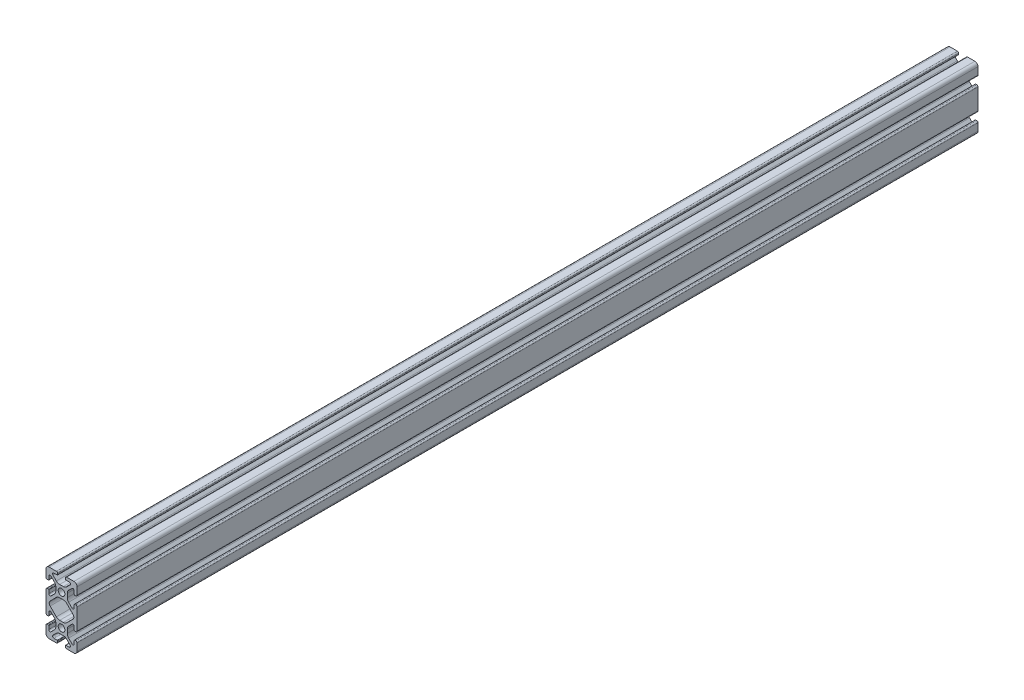
SolidWorks part; units mm, degrees
ref_plane "Front Plane" through (0, 0, 0) normal (0, 0, 1) x (1, 0, 0)
ref_plane "Top Plane" through (0, 0, 0) normal (0, 1, 0) x (1, 0, 0)
ref_plane "Right Plane" through (0, 0, 0) normal (1, 0, 0) x (0, 0, -1)
sketch "Sketch1" plane through (0, 0, 0) normal (0, 0, 1) x (1, 0, 0)
  line L0 (0, 10) -> (0, 20) construction
  line L1 (0, 10) -> (10, 10) construction
  line L2 (0, 10) -> (-10, 20) construction
  line L3 (-8, 20) -> (-3.3, 20)
  line L4 (-10, 20) -> (0, 20) construction
  line L6 (-2.8, 18.2) -> (-4.9051, 18.2)
  line L10 (0, 13.7) -> (-1.2022, 13.7)
  line L11 (-3.3236, 14.5787) -> (-5.5025, 16.7576)
  line L24 (0, 10) -> (-10, 10) construction
  line L25 (-10, 10) -> (0, 10) construction
  line L27 (-10, 0) -> (-10, 20) construction
  line L28 (0, 20) -> (10, 20) construction
  line L29 (-2.5, 18.5) -> (-2.5, 19.2)
  line L30 (-10, -20) -> (10, -20) construction
  line L31 (0, 20) -> (0, -20) construction
  arc A0 (-9.4142, 19.4142) -> (-8, 20) centre (-8, 18) cw
  arc A5 (-3.3, 20) -> (-2.5, 19.2) centre (-3.3, 19.2) cw
  arc A6 (-1.2022, 13.7) -> (-3.3236, 14.5787) centre (-1.2022, 16.7) cw
  circle A16 centre (0, 10) radius 2.15
  arc A18 (-5.5025, 16.7576) -> (-4.9051, 18.2) centre (-4.9051, 17.3551) cw
  arc A20 (-2.8, 18.2) -> (-2.5, 18.5) centre (-2.8, 18.5) ccw
  point P15 (0, -20)
  point P24 (0, 0)
  point P42 (-2.4449, 13.7)
  point P80 (-10, 10)
  dimension "D11" = 2
  dimension "D15" = 3
  dimension "Center Hole Diameter" = 4.3
  dimension "D7" = 0.8
  dimension "D8" = 0.3
  dimension "D4" = 0.8449
  dimension "D1" = 45
  dimension "Rail Width" = 20
  dimension "T-Slot Depth" = 6.3
  dimension "D9" = 1.8
  dimension "D23" = 7.4
  dimension "D5" = 11.5
  dimension "T-Slot Width" = 5
  dimension "D3" = 1.775
  dimension "D6" = 9.8102
  dimension "Rail Height" = 40
sketch "Sketch2" plane through (0, 0, 0) normal (1, 0, 0) x (0, 0, -1)
  line L0 (-304.8, 0) -> (304.8, 0)
  line L1 (-304.8, -20) -> (-304.8, 20)
  line L2 (0, 10) -> (0, 20) construction
  line L3 (0, 0) -> (0, 20) construction
  line L4 (304.8, -20) -> (304.8, 20)
  line L5 (-10, 10) -> (10, 10) construction
  point P0 (-279.8, 0)
  point P3 (0, 0)
  point P7 (279.8, 0)
  point P11 (-304.8, 0)
  point P14 (304.8, 0)
  point P23 (0, 10)
  dimension "D1" = 25
  dimension "Length" = 609.6
sketch "Sketch3" plane through (0, 0, 0) normal (0, 0, 1) x (1, 0, 0)
  line L0 (-2.5, 18.5) -> (-2.5, 19.2) construction
  line L1 (0, 10) -> (-10, 20) construction
  line L2 (0, 10) -> (-10, 20) construction
  line L5 (-8, 20) -> (-3.3, 20) construction
  line L6 (-2.8, 18.2) -> (-4.9051, 18.2) construction
  line L7 (-8.5, 7.5) -> (-9.2, 7.5)
  line L17 (-2.5, 18.5) -> (-2.5, 19.2)
  line L19 (-2.8, 18.2) -> (-4.9051, 18.2)
  line L21 (-3.7, 10) -> (0, 10) construction
  line L22 (-3.7, 8.7978) -> (-3.7, 11.2022)
  line L23 (-4.5787, 13.3236) -> (-6.7576, 15.5025)
  line L42 (-3.3236, 14.5787) -> (-5.5025, 16.7576) construction
  line L43 (0, 13.7) -> (-1.2022, 13.7) construction
  line L44 (-8, 20) -> (-3.3, 20)
  line L47 (-3.3236, 14.5787) -> (-5.5025, 16.7576)
  line L48 (1.2022, 13.7) -> (-1.2022, 13.7)
  line L59 (0, 13.7) -> (0, 12.15) construction
  line L60 (-10, 18) -> (-10, 13.3)
  line L61 (-8.2, 12.8) -> (-8.2, 14.9051)
  line L62 (-8.5, 12.5) -> (-9.2, 12.5)
  line L63 (-8.2, 7.2) -> (-8.2, 5.0949)
  line L64 (-10, 0) -> (-10, 6.7)
  line L65 (1.2022, 6.3) -> (-1.2022, 6.3)
  line L66 (-3.3236, 5.4213) -> (-7.3307, 1.4142)
  line L68 (-4.5787, 6.6764) -> (-6.7576, 4.4975)
  line L73 (10, 0) -> (-10, 0) construction
  line L78 (4.5787, 6.6764) -> (6.7576, 4.4975)
  line L79 (3.3236, 5.4213) -> (7.3307, 1.4142)
  line L81 (10, 0) -> (10, 6.7)
  line L82 (8.2, 7.2) -> (8.2, 5.0949)
  line L83 (8.5, 12.5) -> (9.2, 12.5)
  line L84 (8.2, 12.8) -> (8.2, 14.9051)
  line L85 (10, 18) -> (10, 13.3)
  line L87 (3.3236, 14.5787) -> (5.5025, 16.7576)
  line L88 (8, 20) -> (3.3, 20)
  line L89 (4.5787, 13.3236) -> (6.7576, 15.5025)
  line L90 (3.7, 8.7978) -> (3.7, 11.2022)
  line L91 (2.8, 18.2) -> (4.9051, 18.2)
  line L92 (2.5, 18.5) -> (2.5, 19.2)
  line L93 (8.5, 7.5) -> (9.2, 7.5)
  line L94 (-10, 0) -> (-7.9165, 0)
  line L96 (7.9165, 0) -> (10, 0)
  arc A0 (-8, 20) -> (-9.4142, 19.4142) centre (-8, 18) ccw construction
  arc A1 (-2.8, 18.2) -> (-2.5, 18.5) centre (-2.8, 18.5) ccw construction
  arc A3 (-2.8, 18.2) -> (-2.5, 18.5) centre (-2.8, 18.5) ccw
  arc A5 (-8, 20) -> (-10, 18) centre (-8, 18) ccw
  arc A10 (-3.3236, 5.4213) -> (-1.2022, 6.3) centre (-1.2022, 3.3) cw
  circle A13 centre (0, 10) radius 2.15 construction
  circle A14 centre (0, 10) radius 2.15
  arc A15 (-4.5787, 13.3236) -> (-3.7, 11.2022) centre (-6.7, 11.2022) cw
  arc A16 (-8.2, 14.9051) -> (-6.7576, 15.5025) centre (-7.3551, 14.9051) cw
  arc A17 (-9.2, 12.5) -> (-10, 13.3) centre (-9.2, 13.3) cw
  arc A18 (-8.2, 12.8) -> (-8.5, 12.5) centre (-8.5, 12.8) cw
  arc A36 (-2.5, 19.2) -> (-3.3, 20) centre (-3.3, 19.2) ccw construction
  arc A38 (-4.9051, 18.2) -> (-5.5025, 16.7576) centre (-4.9051, 17.3551) ccw construction
  arc A39 (-3.3236, 14.5787) -> (-1.2022, 13.7) centre (-1.2022, 16.7) ccw construction
  arc A41 (-2.5, 19.2) -> (-3.3, 20) centre (-3.3, 19.2) ccw
  arc A43 (-4.9051, 18.2) -> (-5.5025, 16.7576) centre (-4.9051, 17.3551) ccw
  arc A44 (-3.3236, 14.5787) -> (-1.2022, 13.7) centre (-1.2022, 16.7) ccw
  arc A47 (-8.2, 7.2) -> (-8.5, 7.5) centre (-8.5, 7.2) ccw
  arc A48 (-9.2, 7.5) -> (-10, 6.7) centre (-9.2, 6.7) ccw
  arc A49 (-8.2, 5.0949) -> (-6.7576, 4.4975) centre (-7.3551, 5.0949) ccw
  arc A50 (-4.5787, 6.6764) -> (-3.7, 8.7978) centre (-6.7, 8.7978) ccw
  arc A54 (-7.9165, 0) -> (-7.3307, 1.4142) centre (-5.9165, 0) cw
  arc A57 (7.9165, 0) -> (7.3307, 1.4142) centre (5.9165, 0) ccw
  arc A58 (4.5787, 6.6764) -> (3.7, 8.7978) centre (6.7, 8.7978) cw
  arc A59 (8.2, 5.0949) -> (6.7576, 4.4975) centre (7.3551, 5.0949) cw
  arc A60 (9.2, 7.5) -> (10, 6.7) centre (9.2, 6.7) cw
  arc A61 (8.2, 7.2) -> (8.5, 7.5) centre (8.5, 7.2) cw
  arc A62 (3.3236, 14.5787) -> (1.2022, 13.7) centre (1.2022, 16.7) cw
  arc A63 (4.9051, 18.2) -> (5.5025, 16.7576) centre (4.9051, 17.3551) cw
  arc A64 (2.5, 19.2) -> (3.3, 20) centre (3.3, 19.2) cw
  arc A65 (8.2, 12.8) -> (8.5, 12.5) centre (8.5, 12.8) ccw
  arc A66 (9.2, 12.5) -> (10, 13.3) centre (9.2, 13.3) ccw
  arc A67 (8.2, 14.9051) -> (6.7576, 15.5025) centre (7.3551, 14.9051) ccw
  arc A68 (4.5787, 13.3236) -> (3.7, 11.2022) centre (6.7, 11.2022) ccw
  arc A70 (3.3236, 5.4213) -> (1.2022, 6.3) centre (1.2022, 3.3) ccw
  arc A71 (8, 20) -> (10, 18) centre (8, 18) cw
  arc A72 (2.8, 18.2) -> (2.5, 18.5) centre (2.8, 18.5) cw
  point P59 (-10, 2)
  point P71 (0, 0)
  point P116 (0, 6.3)
extrude "Boss-Extrude1" add sketch "Sketch3" along normal mid plane 609.6
pattern_circular "CirPattern1" count 2 over 360 about axis through (0, 0, 0) along (0, 0, 1) of "Boss-Extrude1"
sketch "Sketch4" plane through (0, 0, 304.8) normal (0, 0, 1) x (1, 0, 0)
  line L0 (7.3307, -1.4142) -> (3.3236, -5.4213) construction
  line L1 (-3.3236, -5.4213) -> (-7.3307, -1.4142) construction
  line L2 (1.2022, -6.3) -> (-1.2022, -6.3) construction
  line L3 (3.3236, 5.4213) -> (7.3307, 1.4142) construction
  line L4 (-1.2022, 6.3) -> (1.2022, 6.3) construction
  line L5 (-7.3307, 1.4142) -> (-3.3236, 5.4213) construction
  line L6 (7.3307, -1.4142) -> (3.3236, -5.4213)
  line L7 (-3.3236, -5.4213) -> (-7.3307, -1.4142)
  line L8 (1.2022, -6.3) -> (-1.2022, -6.3)
  line L9 (3.3236, 5.4213) -> (7.3307, 1.4142)
  line L10 (-1.2022, 6.3) -> (1.2022, 6.3)
  line L11 (-7.3307, 1.4142) -> (-3.3236, 5.4213)
  line L52 (-2.5, 18.5) -> (-2.5, 19.2)
  line L53 (-3.3, 20) -> (-8, 20)
  line L54 (-10, 18) -> (-10, 13.3)
  line L55 (-9.2, 12.5) -> (-8.5, 12.5)
  line L56 (-8.2, 12.8) -> (-8.2, 14.9051)
  line L57 (-6.7576, 15.5025) -> (-4.5787, 13.3236)
  line L58 (-3.7, 11.2022) -> (-3.7, 8.7978)
  line L59 (-4.5787, 6.6764) -> (-6.7576, 4.4975)
  line L60 (-8.2, 5.0949) -> (-8.2, 7.2)
  line L61 (-8.5, 7.5) -> (-9.2, 7.5)
  line L62 (-10, 6.7) -> (-10, -6.7)
  line L63 (-9.2, -7.5) -> (-8.5, -7.5)
  line L64 (-8.2, -7.2) -> (-8.2, -5.0949)
  line L65 (-6.7576, -4.4975) -> (-4.5787, -6.6764)
  line L66 (-3.7, -8.7978) -> (-3.7, -11.2022)
  line L67 (-4.5787, -13.3236) -> (-6.7576, -15.5025)
  line L68 (-8.2, -14.9051) -> (-8.2, -12.8)
  line L69 (-8.5, -12.5) -> (-9.2, -12.5)
  line L70 (-10, -13.3) -> (-10, -18)
  line L71 (-8, -20) -> (-3.3, -20)
  line L72 (-2.5, -19.2) -> (-2.5, -18.5)
  line L73 (-2.8, -18.2) -> (-4.9051, -18.2)
  line L74 (-5.5025, -16.7576) -> (-3.3236, -14.5787)
  line L75 (-1.2022, -13.7) -> (1.2022, -13.7)
  line L76 (3.3236, -14.5787) -> (5.5025, -16.7576)
  line L77 (4.9051, -18.2) -> (2.8, -18.2)
  line L78 (2.5, -18.5) -> (2.5, -19.2)
  line L79 (3.3, -20) -> (8, -20)
  line L80 (10, -18) -> (10, -13.3)
  line L81 (9.2, -12.5) -> (8.5, -12.5)
  line L82 (8.2, -12.8) -> (8.2, -14.9051)
  line L83 (6.7576, -15.5025) -> (4.5787, -13.3236)
  line L84 (3.7, -11.2022) -> (3.7, -8.7978)
  line L85 (4.5787, -6.6764) -> (6.7576, -4.4975)
  line L86 (8.2, -5.0949) -> (8.2, -7.2)
  line L87 (8.5, -7.5) -> (9.2, -7.5)
  line L88 (10, -6.7) -> (10, 6.7)
  line L89 (9.2, 7.5) -> (8.5, 7.5)
  line L90 (8.2, 7.2) -> (8.2, 5.0949)
  line L91 (6.7576, 4.4975) -> (4.5787, 6.6764)
  line L92 (3.7, 8.7978) -> (3.7, 11.2022)
  line L93 (4.5787, 13.3236) -> (6.7576, 15.5025)
  line L94 (8.2, 14.9051) -> (8.2, 12.8)
  line L95 (8.5, 12.5) -> (9.2, 12.5)
  line L96 (10, 13.3) -> (10, 18)
  line L97 (8, 20) -> (3.3, 20)
  line L98 (2.5, 19.2) -> (2.5, 18.5)
  line L99 (2.8, 18.2) -> (4.9051, 18.2)
  line L100 (5.5025, 16.7576) -> (3.3236, 14.5787)
  line L101 (1.2022, 13.7) -> (-1.2022, 13.7)
  line L102 (-3.3236, 14.5787) -> (-5.5025, 16.7576)
  line L103 (-4.9051, 18.2) -> (-2.8, 18.2)
  line L104 (-2.5, 18.5) -> (-2.5, 19.2)
  line L105 (-3.3, 20) -> (-8, 20)
  line L106 (-10, 18) -> (-10, 13.3)
  line L107 (-9.2, 12.5) -> (-8.5, 12.5)
  line L108 (-8.2, 12.8) -> (-8.2, 14.9051)
  line L109 (-6.7576, 15.5025) -> (-4.5787, 13.3236)
  line L110 (-3.7, 11.2022) -> (-3.7, 8.7978)
  line L111 (-4.5787, 6.6764) -> (-6.7576, 4.4975)
  line L112 (-8.2, 5.0949) -> (-8.2, 7.2)
  line L113 (-8.5, 7.5) -> (-9.2, 7.5)
  line L114 (-10, 6.7) -> (-10, -6.7)
  line L115 (-9.2, -7.5) -> (-8.5, -7.5)
  line L116 (-8.2, -7.2) -> (-8.2, -5.0949)
  line L117 (-6.7576, -4.4975) -> (-4.5787, -6.6764)
  line L118 (-3.7, -8.7978) -> (-3.7, -11.2022)
  line L119 (-4.5787, -13.3236) -> (-6.7576, -15.5025)
  line L120 (-8.2, -14.9051) -> (-8.2, -12.8)
  line L121 (-8.5, -12.5) -> (-9.2, -12.5)
  line L122 (-10, -13.3) -> (-10, -18)
  line L123 (-8, -20) -> (-3.3, -20)
  line L124 (-2.5, -19.2) -> (-2.5, -18.5)
  line L125 (-2.8, -18.2) -> (-4.9051, -18.2)
  line L126 (-5.5025, -16.7576) -> (-3.3236, -14.5787)
  line L127 (-1.2022, -13.7) -> (1.2022, -13.7)
  line L128 (3.3236, -14.5787) -> (5.5025, -16.7576)
  line L129 (4.9051, -18.2) -> (2.8, -18.2)
  line L130 (2.5, -18.5) -> (2.5, -19.2)
  line L131 (3.3, -20) -> (8, -20)
  line L132 (10, -18) -> (10, -13.3)
  line L133 (9.2, -12.5) -> (8.5, -12.5)
  line L134 (8.2, -12.8) -> (8.2, -14.9051)
  line L135 (6.7576, -15.5025) -> (4.5787, -13.3236)
  line L136 (3.7, -11.2022) -> (3.7, -8.7978)
  line L137 (4.5787, -6.6764) -> (6.7576, -4.4975)
  line L138 (8.2, -5.0949) -> (8.2, -7.2)
  line L139 (8.5, -7.5) -> (9.2, -7.5)
  line L140 (10, -6.7) -> (10, 6.7)
  line L141 (9.2, 7.5) -> (8.5, 7.5)
  line L142 (8.2, 7.2) -> (8.2, 5.0949)
  line L143 (6.7576, 4.4975) -> (4.5787, 6.6764)
  line L144 (3.7, 8.7978) -> (3.7, 11.2022)
  line L145 (4.5787, 13.3236) -> (6.7576, 15.5025)
  line L146 (8.2, 14.9051) -> (8.2, 12.8)
  line L147 (8.5, 12.5) -> (9.2, 12.5)
  line L148 (10, 13.3) -> (10, 18)
  line L149 (8, 20) -> (3.3, 20)
  line L150 (2.5, 19.2) -> (2.5, 18.5)
  line L151 (2.8, 18.2) -> (4.9051, 18.2)
  line L152 (5.5025, 16.7576) -> (3.3236, 14.5787)
  line L153 (1.2022, 13.7) -> (-1.2022, 13.7)
  line L154 (-3.3236, 14.5787) -> (-5.5025, 16.7576)
  line L155 (-4.9051, 18.2) -> (-2.8, 18.2)
  circle A0 centre (0, 10) radius 2.15 construction
  arc A1 (-7.3307, 1.4142) -> (-7.3307, -1.4142) centre (-5.9165, 0) ccw construction
  arc A2 (-3.3236, -5.4213) -> (-1.2022, -6.3) centre (-1.2022, -3.3) ccw construction
  arc A3 (1.2022, -6.3) -> (3.3236, -5.4213) centre (1.2022, -3.3) ccw construction
  circle A4 centre (0, -10) radius 2.15 construction
  arc A5 (7.3307, -1.4142) -> (7.3307, 1.4142) centre (5.9165, 0) ccw construction
  arc A6 (3.3236, 5.4213) -> (1.2022, 6.3) centre (1.2022, 3.3) ccw construction
  arc A7 (-1.2022, 6.3) -> (-3.3236, 5.4213) centre (-1.2022, 3.3) ccw construction
  circle A8 centre (0, 10) radius 2.15
  arc A9 (-7.3307, 1.4142) -> (-7.3307, -1.4142) centre (-5.9165, 0) ccw
  arc A10 (-3.3236, -5.4213) -> (-1.2022, -6.3) centre (-1.2022, -3.3) ccw
  arc A11 (1.2022, -6.3) -> (3.3236, -5.4213) centre (1.2022, -3.3) ccw
  circle A12 centre (0, -10) radius 2.15
  arc A13 (7.3307, -1.4142) -> (7.3307, 1.4142) centre (5.9165, 0) ccw
  arc A14 (3.3236, 5.4213) -> (1.2022, 6.3) centre (1.2022, 3.3) ccw
  arc A15 (-1.2022, 6.3) -> (-3.3236, 5.4213) centre (-1.2022, 3.3) ccw
  arc A52 (-2.8, 18.2) -> (-2.5, 18.5) centre (-2.8, 18.5) ccw
  arc A53 (-2.5, 19.2) -> (-3.3, 20) centre (-3.3, 19.2) ccw
  arc A54 (-8, 20) -> (-10, 18) centre (-8, 18) ccw
  arc A55 (-10, 13.3) -> (-9.2, 12.5) centre (-9.2, 13.3) ccw
  arc A56 (-8.5, 12.5) -> (-8.2, 12.8) centre (-8.5, 12.8) ccw
  arc A57 (-6.7576, 15.5025) -> (-8.2, 14.9051) centre (-7.3551, 14.9051) ccw
  arc A58 (-3.7, 11.2022) -> (-4.5787, 13.3236) centre (-6.7, 11.2022) ccw
  arc A59 (-4.5787, 6.6764) -> (-3.7, 8.7978) centre (-6.7, 8.7978) ccw
  arc A60 (-8.2, 5.0949) -> (-6.7576, 4.4975) centre (-7.3551, 5.0949) ccw
  arc A61 (-8.2, 7.2) -> (-8.5, 7.5) centre (-8.5, 7.2) ccw
  arc A62 (-9.2, 7.5) -> (-10, 6.7) centre (-9.2, 6.7) ccw
  arc A63 (-10, -6.7) -> (-9.2, -7.5) centre (-9.2, -6.7) ccw
  arc A64 (-8.5, -7.5) -> (-8.2, -7.2) centre (-8.5, -7.2) ccw
  arc A65 (-6.7576, -4.4975) -> (-8.2, -5.0949) centre (-7.3551, -5.0949) ccw
  arc A66 (-3.7, -8.7978) -> (-4.5787, -6.6764) centre (-6.7, -8.7978) ccw
  arc A67 (-4.5787, -13.3236) -> (-3.7, -11.2022) centre (-6.7, -11.2022) ccw
  arc A68 (-8.2, -14.9051) -> (-6.7576, -15.5025) centre (-7.3551, -14.9051) ccw
  arc A69 (-8.2, -12.8) -> (-8.5, -12.5) centre (-8.5, -12.8) ccw
  arc A70 (-9.2, -12.5) -> (-10, -13.3) centre (-9.2, -13.3) ccw
  arc A71 (-10, -18) -> (-8, -20) centre (-8, -18) ccw
  arc A72 (-3.3, -20) -> (-2.5, -19.2) centre (-3.3, -19.2) ccw
  arc A73 (-2.5, -18.5) -> (-2.8, -18.2) centre (-2.8, -18.5) ccw
  arc A74 (-5.5025, -16.7576) -> (-4.9051, -18.2) centre (-4.9051, -17.3551) ccw
  arc A75 (-1.2022, -13.7) -> (-3.3236, -14.5787) centre (-1.2022, -16.7) ccw
  arc A76 (3.3236, -14.5787) -> (1.2022, -13.7) centre (1.2022, -16.7) ccw
  arc A77 (4.9051, -18.2) -> (5.5025, -16.7576) centre (4.9051, -17.3551) ccw
  arc A78 (2.8, -18.2) -> (2.5, -18.5) centre (2.8, -18.5) ccw
  arc A79 (2.5, -19.2) -> (3.3, -20) centre (3.3, -19.2) ccw
  arc A80 (8, -20) -> (10, -18) centre (8, -18) ccw
  arc A81 (10, -13.3) -> (9.2, -12.5) centre (9.2, -13.3) ccw
  arc A82 (8.5, -12.5) -> (8.2, -12.8) centre (8.5, -12.8) ccw
  arc A83 (6.7576, -15.5025) -> (8.2, -14.9051) centre (7.3551, -14.9051) ccw
  arc A84 (3.7, -11.2022) -> (4.5787, -13.3236) centre (6.7, -11.2022) ccw
  arc A85 (4.5787, -6.6764) -> (3.7, -8.7978) centre (6.7, -8.7978) ccw
  arc A86 (8.2, -5.0949) -> (6.7576, -4.4975) centre (7.3551, -5.0949) ccw
  arc A87 (8.2, -7.2) -> (8.5, -7.5) centre (8.5, -7.2) ccw
  arc A88 (9.2, -7.5) -> (10, -6.7) centre (9.2, -6.7) ccw
  arc A89 (10, 6.7) -> (9.2, 7.5) centre (9.2, 6.7) ccw
  arc A90 (8.5, 7.5) -> (8.2, 7.2) centre (8.5, 7.2) ccw
  arc A91 (6.7576, 4.4975) -> (8.2, 5.0949) centre (7.3551, 5.0949) ccw
  arc A92 (3.7, 8.7978) -> (4.5787, 6.6764) centre (6.7, 8.7978) ccw
  arc A93 (4.5787, 13.3236) -> (3.7, 11.2022) centre (6.7, 11.2022) ccw
  arc A94 (8.2, 14.9051) -> (6.7576, 15.5025) centre (7.3551, 14.9051) ccw
  arc A95 (8.2, 12.8) -> (8.5, 12.5) centre (8.5, 12.8) ccw
  arc A96 (9.2, 12.5) -> (10, 13.3) centre (9.2, 13.3) ccw
  arc A97 (10, 18) -> (8, 20) centre (8, 18) ccw
  arc A98 (3.3, 20) -> (2.5, 19.2) centre (3.3, 19.2) ccw
  arc A99 (2.5, 18.5) -> (2.8, 18.2) centre (2.8, 18.5) ccw
  arc A100 (5.5025, 16.7576) -> (4.9051, 18.2) centre (4.9051, 17.3551) ccw
  arc A101 (1.2022, 13.7) -> (3.3236, 14.5787) centre (1.2022, 16.7) ccw
  arc A102 (-3.3236, 14.5787) -> (-1.2022, 13.7) centre (-1.2022, 16.7) ccw
  arc A103 (-4.9051, 18.2) -> (-5.5025, 16.7576) centre (-4.9051, 17.3551) ccw
  arc A104 (-2.8, 18.2) -> (-2.5, 18.5) centre (-2.8, 18.5) ccw
  arc A105 (-2.5, 19.2) -> (-3.3, 20) centre (-3.3, 19.2) ccw
  arc A106 (-8, 20) -> (-10, 18) centre (-8, 18) ccw
  arc A107 (-10, 13.3) -> (-9.2, 12.5) centre (-9.2, 13.3) ccw
  arc A108 (-8.5, 12.5) -> (-8.2, 12.8) centre (-8.5, 12.8) ccw
  arc A109 (-6.7576, 15.5025) -> (-8.2, 14.9051) centre (-7.3551, 14.9051) ccw
  arc A110 (-3.7, 11.2022) -> (-4.5787, 13.3236) centre (-6.7, 11.2022) ccw
  arc A111 (-4.5787, 6.6764) -> (-3.7, 8.7978) centre (-6.7, 8.7978) ccw
  arc A112 (-8.2, 5.0949) -> (-6.7576, 4.4975) centre (-7.3551, 5.0949) ccw
  arc A113 (-8.2, 7.2) -> (-8.5, 7.5) centre (-8.5, 7.2) ccw
  arc A114 (-9.2, 7.5) -> (-10, 6.7) centre (-9.2, 6.7) ccw
  arc A115 (-10, -6.7) -> (-9.2, -7.5) centre (-9.2, -6.7) ccw
  arc A116 (-8.5, -7.5) -> (-8.2, -7.2) centre (-8.5, -7.2) ccw
  arc A117 (-6.7576, -4.4975) -> (-8.2, -5.0949) centre (-7.3551, -5.0949) ccw
  arc A118 (-3.7, -8.7978) -> (-4.5787, -6.6764) centre (-6.7, -8.7978) ccw
  arc A119 (-4.5787, -13.3236) -> (-3.7, -11.2022) centre (-6.7, -11.2022) ccw
  arc A120 (-8.2, -14.9051) -> (-6.7576, -15.5025) centre (-7.3551, -14.9051) ccw
  arc A121 (-8.2, -12.8) -> (-8.5, -12.5) centre (-8.5, -12.8) ccw
  arc A122 (-9.2, -12.5) -> (-10, -13.3) centre (-9.2, -13.3) ccw
  arc A123 (-10, -18) -> (-8, -20) centre (-8, -18) ccw
  arc A124 (-3.3, -20) -> (-2.5, -19.2) centre (-3.3, -19.2) ccw
  arc A125 (-2.5, -18.5) -> (-2.8, -18.2) centre (-2.8, -18.5) ccw
  arc A126 (-5.5025, -16.7576) -> (-4.9051, -18.2) centre (-4.9051, -17.3551) ccw
  arc A127 (-1.2022, -13.7) -> (-3.3236, -14.5787) centre (-1.2022, -16.7) ccw
  arc A128 (3.3236, -14.5787) -> (1.2022, -13.7) centre (1.2022, -16.7) ccw
  arc A129 (4.9051, -18.2) -> (5.5025, -16.7576) centre (4.9051, -17.3551) ccw
  arc A130 (2.8, -18.2) -> (2.5, -18.5) centre (2.8, -18.5) ccw
  arc A131 (2.5, -19.2) -> (3.3, -20) centre (3.3, -19.2) ccw
  arc A132 (8, -20) -> (10, -18) centre (8, -18) ccw
  arc A133 (10, -13.3) -> (9.2, -12.5) centre (9.2, -13.3) ccw
  arc A134 (8.5, -12.5) -> (8.2, -12.8) centre (8.5, -12.8) ccw
  arc A135 (6.7576, -15.5025) -> (8.2, -14.9051) centre (7.3551, -14.9051) ccw
  arc A136 (3.7, -11.2022) -> (4.5787, -13.3236) centre (6.7, -11.2022) ccw
  arc A137 (4.5787, -6.6764) -> (3.7, -8.7978) centre (6.7, -8.7978) ccw
  arc A138 (8.2, -5.0949) -> (6.7576, -4.4975) centre (7.3551, -5.0949) ccw
  arc A139 (8.2, -7.2) -> (8.5, -7.5) centre (8.5, -7.2) ccw
  arc A140 (9.2, -7.5) -> (10, -6.7) centre (9.2, -6.7) ccw
  arc A141 (10, 6.7) -> (9.2, 7.5) centre (9.2, 6.7) ccw
  arc A142 (8.5, 7.5) -> (8.2, 7.2) centre (8.5, 7.2) ccw
  arc A143 (6.7576, 4.4975) -> (8.2, 5.0949) centre (7.3551, 5.0949) ccw
  arc A144 (3.7, 8.7978) -> (4.5787, 6.6764) centre (6.7, 8.7978) ccw
  arc A145 (4.5787, 13.3236) -> (3.7, 11.2022) centre (6.7, 11.2022) ccw
  arc A146 (8.2, 14.9051) -> (6.7576, 15.5025) centre (7.3551, 14.9051) ccw
  arc A147 (8.2, 12.8) -> (8.5, 12.5) centre (8.5, 12.8) ccw
  arc A148 (9.2, 12.5) -> (10, 13.3) centre (9.2, 13.3) ccw
  arc A149 (10, 18) -> (8, 20) centre (8, 18) ccw
  arc A150 (3.3, 20) -> (2.5, 19.2) centre (3.3, 19.2) ccw
  arc A151 (2.5, 18.5) -> (2.8, 18.2) centre (2.8, 18.5) ccw
  arc A152 (5.5025, 16.7576) -> (4.9051, 18.2) centre (4.9051, 17.3551) ccw
  arc A153 (1.2022, 13.7) -> (3.3236, 14.5787) centre (1.2022, 16.7) ccw
  arc A154 (-3.3236, 14.5787) -> (-1.2022, 13.7) centre (-1.2022, 16.7) ccw
  arc A155 (-4.9051, 18.2) -> (-5.5025, 16.7576) centre (-4.9051, 17.3551) ccw
  dimension "D1" = 0
extrude "Cut-Extrude1" cut sketch "Sketch4" against normal blind 29.07
equation "\"D1@Sketch2\"=\"Rail Width@Sketch1\"*1.25"
equation "\"D1@Boss-Extrude1\" = \"Length@Sketch2\""
